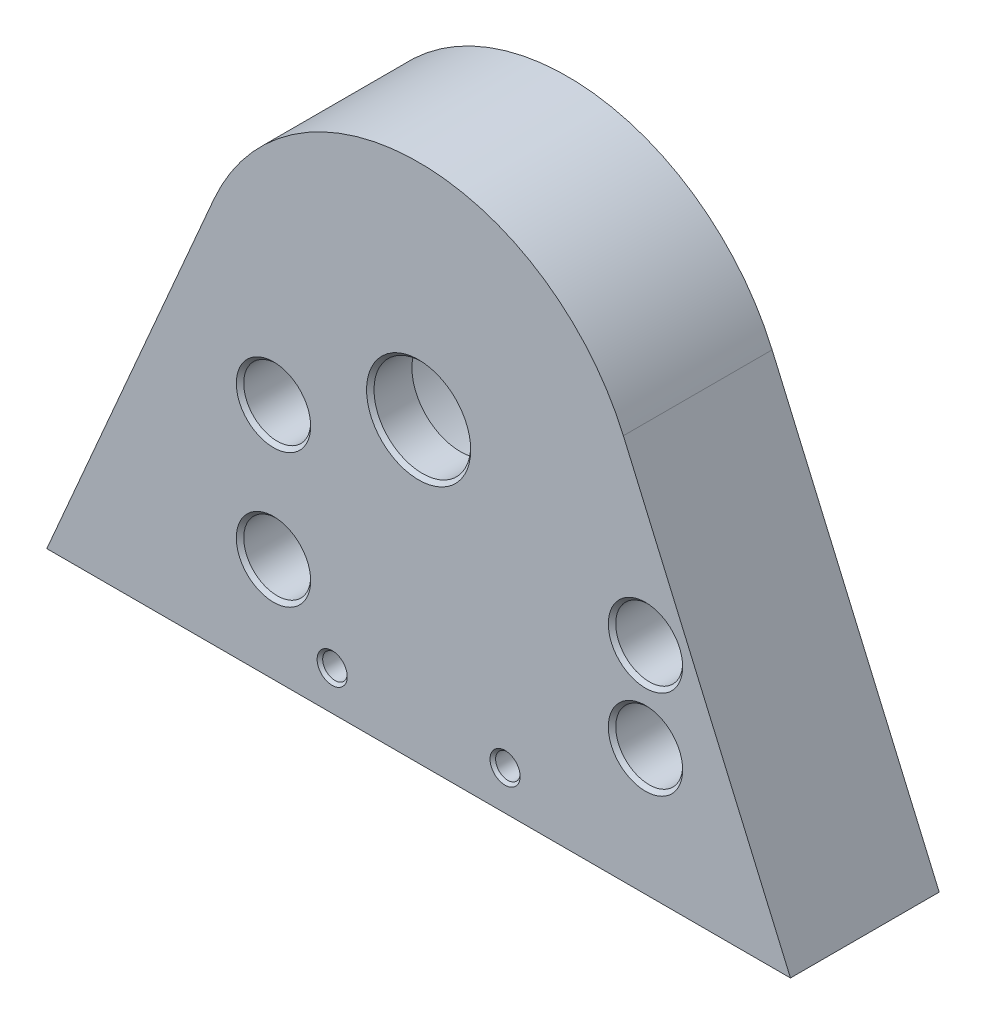
SolidWorks part; units mm, degrees
material "3.3547 (EN-AW 5083)"
ref_plane "Ebene vorne" through (0, 0, 0) normal (0, 0, 1) x (1, 0, 0)
ref_plane "Ebene oben" through (0, 0, 0) normal (0, 1, 0) x (1, 0, 0)
ref_plane "Ebene rechts" through (0, 0, 0) normal (1, 0, 0) x (0, 0, -1)
sketch "Skizze1" plane through (0, 0, 0) normal (0, 0, 1) x (1, 0, 0)
  line L0 (0, 0) -> (100, 0)
  line L1 (50, 0) -> (50, 111.8449) construction
  line L2 (22.4677, 51.9153) -> (0, 0)
  line L3 (77.5323, 51.9153) -> (100, 0)
  line L4 (60.9179, 40) -> (38.7984, 40) construction
  arc A0 (77.5323, 51.9153) -> (22.4677, 51.9153) centre (50, 40) ccw
  circle A1 centre (50, 40) radius 6.5
  dimension "D1" = 100
  dimension "D2" = 40
  dimension "D3" = 30
extrude "Aufsatz-Linear austragen1" add sketch "Skizze1" along normal blind 20
sketch "Skizze4" plane through (0, 0, 0) normal (0, 0, -1) x (-1, 0, 0)
  circle A0 centre (-50, 40) radius 15
extrude "Schnitt-Linear austragen2" cut sketch "Skizze4" against normal blind 14.4
sketch "Skizze5" plane through (0, 0, 20) normal (0, 0, 1) x (1, 0, 0)
  line L0 (0, 0) -> (100, 0) construction
  circle A0 centre (38.375, 5.29) radius 1
  circle A1 centre (61.625, 5.29) radius 1
  circle A2 centre (50, 40) radius 6.5 construction
  dimension "D1" = 5.29
  dimension "D2" = 5.29
  dimension "D3" = 11.625
  dimension "D4" = 11.625
hole_wizard "M4 Gewindebohrung1" positions "3D-Skizze1" profile "Skizze6" tap size "M4" standard "DIN"
sketch3d "3D-Skizze1"
  point P0 (38.375, 5.29, 20)
  point P3 (61.625, 5.29, 20)
sketch "Skizze6" plane through (38.375, 5.29, 20) normal (1, 0, 0) x (0, -1, 0)
  line L0 (0, 0) -> (0, 12.4914)
  line L1 (0, 12.4914) -> (1.65, 11.5)
  line L2 (1.65, 11.5) -> (1.65, 0.375)
  line L3 (1.65, 0.375) -> (2.025, 0)
  line L5 (2.025, 0) -> (0, 0)
  line L6 (-1.65, 0.375) -> (-2.025, 0) construction
  line L10 (0, 12.4914) -> (-1.65, 11.5) construction
  line L11 (0, -6.35) -> (0, 107.95) construction
  dimension "Bohrerdurchmesser" = 3.3
  dimension "Bohrungstiefe" = 11.5
  dimension "Senkdurchmesser (Oben)" = 4.05
  dimension "Senkwinkel (Oben)" = 90
  dimension "Spitzenwinkel" = 118
cosmetic thread "Bohrungsgewinde6" parameters "D1"=8, "D2"=4
cosmetic thread "Bohrungsgewinde7" parameters "D1"=8, "D2"=4
sketch "Skizze7" plane through (0, 0, 0) normal (0, 0, -1) x (-1, 0, 0)
  circle A0 centre (-30.482, 32) radius 2.25
  circle A1 centre (-30.482, 14) radius 2.25
extrude "Schnitt-Linear austragen3" cut sketch "Skizze7" against normal blind 20
sketch "Skizze8" plane through (0, 0, 20) normal (0, 0, 1) x (1, 0, 0)
  circle A0 centre (30.482, 32) radius 4.5
  circle A1 centre (30.482, 14) radius 4.5
extrude "Schnitt-Linear austragen4" cut sketch "Skizze8" against normal blind 10
chamfer "Fase1" distance 0.5 angle 45 3 edges at (34.982, 14, 20) (56.5, 40, 20) (34.982, 32, 20)
chamfer "Fase2" distance 0.5 angle 45 3 edges at (28.232, 14, 0) (28.232, 32, 0) (35, 40, 0)
sketch "Skizze9" plane through (0, 0, 0) normal (0, 0, -1) x (-1, 0, 0)
  circle A0 centre (-50, 60) radius 1.6
  circle A1 centre (-70, 40) radius 1.6
  circle A2 centre (-50, 20) radius 1.6
extrude "Schnitt-Linear austragen5" cut sketch "Skizze9" against normal blind 15
hole_wizard "M4 Gewindebohrung2" positions "3D-Skizze2" profile "Skizze10" tap size "M4" standard "DIN"
sketch3d "3D-Skizze2"
  line L0 (70, 40, 15) -> (70, 40, 0) construction
  line L1 (50, 60, 15) -> (50, 60, 0) construction
  line L2 (50, 20, 15) -> (50, 20, 0) construction
  point P0 (70, 40, 0)
  point P4 (50, 60, 0)
  point P8 (50, 20, 0)
sketch "Skizze10" plane through (70, 40, 0) normal (1, 0, 0) x (0, 1, 0)
  line L0 (0, 0) -> (0, 12.4914)
  line L1 (0, 12.4914) -> (1.65, 11.5)
  line L2 (1.65, 11.5) -> (1.65, 0.375)
  line L3 (1.65, 0.375) -> (2.025, 0)
  line L5 (2.025, 0) -> (0, 0)
  line L6 (-1.65, 0.375) -> (-2.025, 0) construction
  line L10 (0, 12.4914) -> (-1.65, 11.5) construction
  line L11 (0, -6.35) -> (0, 107.95) construction
  dimension "Bohrerdurchmesser" = 3.3
  dimension "Bohrungstiefe" = 11.5
  dimension "Senkdurchmesser (Oben)" = 4.05
  dimension "Senkwinkel (Oben)" = 90
  dimension "Spitzenwinkel" = 118
cosmetic thread "Bohrungsgewinde3" parameters "D1"=8, "D2"=4
cosmetic thread "Bohrungsgewinde4" parameters "D1"=8, "D2"=4
cosmetic thread "Bohrungsgewinde5" parameters "D1"=8, "D2"=4
sketch "Skizze11" plane through (0, 0, 0) normal (0, 0, -1) x (-1, 0, 0)
  line L0 (0, 0) -> (-100, 0) construction
  circle A0 centre (-80.504, 29) radius 2.25
  circle A1 centre (-80.504, 17) radius 2.25
  dimension "D1" = 17
  dimension "D2" = 29
  dimension "D3" = 19.496
extrude "Schnitt-Linear austragen6" cut sketch "Skizze11" against normal blind 30
sketch "Skizze12" plane through (0, 0, 20) normal (0, 0, 1) x (1, 0, 0)
  circle A0 centre (80.504, 29) radius 4.5
  circle A1 centre (80.504, 17) radius 4.5
extrude "Schnitt-Linear austragen7" cut sketch "Skizze12" against normal blind 10
chamfer "Fase3" distance 0.5 angle 45 2 edges at (85.004, 17, 20) (85.004, 29, 20)
